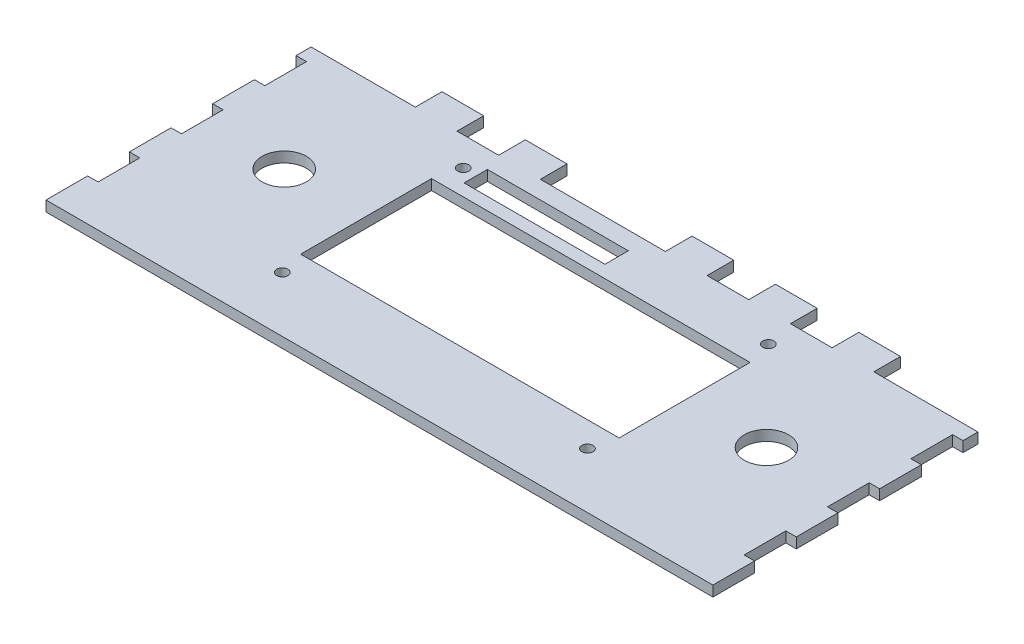
SolidWorks part; units mm, degrees
material "Acrylic (Medium-high impact)"
ref_plane "Front Plane" through (0, 0, 0) normal (0, 0, 1) x (1, 0, 0)
ref_plane "Top Plane" through (0, 0, 0) normal (0, 1, 0) x (1, 0, 0)
ref_plane "Right Plane" through (0, 0, 0) normal (1, 0, 0) x (0, 0, -1)
sketch "Sketch1" plane through (0, 0, 0) normal (0, 1, 0) x (1, 0, 0)
  line L1 (0, 0) -> (203.2, 0)
  line L2 (0, 0) -> (0, 88.9)
  line L3 (0, 88.9) -> (203.2, 88.9)
  line L4 (203.2, 0) -> (203.2, 88.9)
  dimension "D1" = 203.2
  dimension "D2" = 88.9
extrude "Boss-Extrude1" add sketch "Sketch1" along normal blind 3.175
sketch "Sketch2" plane through (0, 3.175, 0) normal (0, 1, 0) x (1, 0, 0)
  line L0 (203.2, 88.9) -> (0, 88.9) construction
  line L1 (19.05, 88.9) -> (31.75, 88.9)
  line L2 (19.05, 88.9) -> (19.05, 80.772)
  line L3 (19.05, 80.772) -> (31.75, 80.772)
  line L4 (31.75, 88.9) -> (31.75, 80.772)
  line L5 (0, 88.9) -> (0, 0) construction
  line L23 (203.2, 0) -> (203.2, 88.9) construction
  line L24 (0, 44.45) -> (203.2, 44.45) construction
  line L45 (0, 50.8) -> (0, 38.1)
  line L46 (0, 76.2) -> (3.175, 76.2)
  line L47 (0, 76.2) -> (0, 63.5)
  line L48 (0, 63.5) -> (3.175, 63.5)
  line L49 (3.175, 76.2) -> (3.175, 63.5)
  line L50 (0, 50.8) -> (3.175, 50.8)
  line L51 (3.175, 50.8) -> (3.175, 38.1)
  line L52 (0, 38.1) -> (3.175, 38.1)
  line L53 (0, 25.4) -> (0, 12.7)
  line L54 (0, 25.4) -> (3.175, 25.4)
  line L55 (3.175, 25.4) -> (3.175, 12.7)
  line L56 (0, 12.7) -> (3.175, 12.7)
  line L57 (44.45, 88.9) -> (44.45, 80.772)
  line L58 (44.45, 88.9) -> (57.15, 88.9)
  line L71 (57.15, 88.9) -> (57.15, 80.772)
  line L72 (44.45, 80.772) -> (57.15, 80.772)
  line L73 (69.85, 88.9) -> (69.85, 80.772)
  line L74 (69.85, 88.9) -> (82.55, 88.9)
  line L75 (82.55, 88.9) -> (82.55, 80.772)
  line L76 (69.85, 80.772) -> (82.55, 80.772)
  line L77 (95.25, 88.9) -> (95.25, 80.772)
  line L78 (95.25, 88.9) -> (107.95, 88.9)
  line L79 (107.95, 88.9) -> (107.95, 80.772)
  line L80 (95.25, 80.772) -> (107.95, 80.772)
  line L81 (120.65, 88.9) -> (120.65, 80.772)
  line L82 (120.65, 88.9) -> (133.35, 88.9)
  line L83 (133.35, 88.9) -> (133.35, 80.772)
  line L84 (120.65, 80.772) -> (133.35, 80.772)
  line L85 (146.05, 88.9) -> (146.05, 80.772)
  line L86 (146.05, 88.9) -> (158.75, 88.9)
  line L87 (158.75, 88.9) -> (158.75, 80.772)
  line L88 (146.05, 80.772) -> (158.75, 80.772)
  line L89 (171.45, 88.9) -> (171.45, 80.772)
  line L90 (171.45, 88.9) -> (184.15, 88.9)
  line L91 (184.15, 88.9) -> (184.15, 80.772)
  line L92 (171.45, 80.772) -> (184.15, 80.772)
  line L97 (196.85, 88.9) -> (196.85, 80.772) [skipped]
  line L98 (196.85, 88.9) -> (209.55, 88.9) [skipped]
  line L99 (209.55, 88.9) -> (209.55, 80.772) [skipped]
  line L100 (196.85, 80.772) -> (209.55, 80.772) [skipped]
  line L129 (101.6, 0) -> (101.6, 88.9) construction
  line L130 (0, 0) -> (203.2, 0) construction
  line L131 (203.2, 12.7) -> (200.025, 12.7)
  line L132 (200.025, 25.4) -> (200.025, 12.7)
  line L133 (203.2, 25.4) -> (200.025, 25.4)
  line L134 (203.2, 25.4) -> (203.2, 12.7)
  line L135 (203.2, 38.1) -> (200.025, 38.1)
  line L136 (200.025, 50.8) -> (200.025, 38.1)
  line L137 (203.2, 50.8) -> (200.025, 50.8)
  line L138 (200.025, 76.2) -> (200.025, 63.5)
  line L139 (203.2, 63.5) -> (200.025, 63.5)
  line L140 (203.2, 76.2) -> (203.2, 63.5)
  line L141 (203.2, 76.2) -> (200.025, 76.2)
  line L142 (203.2, 50.8) -> (203.2, 38.1)
  line L148 (0, 88.9) -> (19.05, 88.9)
  line L149 (0, 88.9) -> (0, 80.772)
  line L150 (0, 80.772) -> (19.05, 80.772)
  line L151 (19.05, 88.9) -> (19.05, 80.772)
  line L152 (184.15, 88.9) -> (203.2, 88.9)
  line L153 (184.15, 88.9) -> (184.15, 80.772)
  line L154 (184.15, 80.772) -> (203.2, 80.772)
  line L155 (203.2, 88.9) -> (203.2, 80.772)
  line L159 (82.55, 88.9) -> (107.95, 88.9)
  line L160 (82.55, 88.9) -> (82.55, 80.772)
  line L161 (82.55, 80.772) -> (107.95, 80.772)
  line L162 (107.95, 88.9) -> (107.95, 80.772)
  point P80 (101.6, 0)
  line M29 (0, 88.9) -> (0, 0)
  line M31 (203.2, 0) -> (203.2, 88.9)
  line M32 (203.2, 88.9) -> (0, 88.9)
  dimension "D1" = 19.05
  dimension "D2" = 12.7
  dimension "D3" = 8.128
  dimension "D5" = 12.7
  dimension "D6" = 12.7
  dimension "D7" = 12.7
  dimension "D8" = 3.175
  dimension "D10" = 12.7
  dimension "D9" = 3
  dimension "D4" = 8
extrude "Cut-Extrude1" cut sketch "Sketch2" against normal through all contours L150 L2 M29 M32 | L4 L2 L3 M32 | L57 L72 L71 M32 | L73 L76 L75 M32 | L81 L84 L83 M32 | L85 L88 L87 M32 | L89 L92 L91 M32 | L91 L154 M31 M32 | L137 L136 L135 M31 | L133 L132 L131 M31 | L56 L55 L54 M29 | L52 L51 L50 M29 | L49 L46 L48 M29 | L75 L161 L77 M32 | L77 L80 L79 M32
sketch "Sketch3" plane through (0, 0, 0) normal (0, -1, 0) x (1, 0, 0)
  line L0 (3.175, -38.1) -> (3.175, -50.8) construction
  line L1 (53.086, -24.511) -> (150.114, -24.511)
  line L2 (53.086, -24.511) -> (53.086, -64.389)
  line L3 (53.086, -64.389) -> (150.114, -64.389)
  line L4 (150.114, -24.511) -> (150.114, -64.389)
  line L6 (0, 0) -> (203.2, 0) construction
  line L7 (59.182, -68.199) -> (102.108, -68.199)
  line L8 (59.182, -68.199) -> (59.182, -75.311)
  line L9 (59.182, -75.311) -> (102.108, -75.311)
  line L10 (102.108, -68.199) -> (102.108, -75.311)
  point P6 (3.175, -44.45)
  point P7 (53.086, -44.45)
  point P8 (101.6, -24.511)
  point P16 (101.6, 0)
  dimension "D1" = 97.028
  dimension "D2" = 39.878
  dimension "D5" = 42.926
  dimension "D6" = 7.112
  dimension "D4" = 3.81
  dimension "D3" = 6.096
extrude "Cut-Extrude2" cut sketch "Sketch3" against normal through all
hole_wizard "M3 Clearance Hole1" positions "Sketch7" profile "Sketch8" hole size "M3" standard "ANSI Metric" end condition through all
sketch "Sketch7" plane through (0, 0, 0) normal (0, -1, 0) x (-1, 0, 0)
  line L1 (-148.082, 72.009) -> (-55.118, 72.009) construction
  line L2 (-148.082, 72.009) -> (-148.082, 16.891) construction
  line L3 (-148.082, 16.891) -> (-55.118, 16.891) construction
  line L4 (-55.118, 72.009) -> (-55.118, 16.891) construction
  line L5 (-53.086, 64.389) -> (-150.114, 64.389) construction
  line L6 (-53.086, 24.511) -> (-53.086, 64.389) construction
  point P0 (-148.082, 72.009)
  point P2 (-148.082, 16.891)
  point P4 (-55.118, 16.891)
  point P6 (-55.118, 72.009)
  point P225 (-101.6, 64.389)
  point P226 (-101.6, 72.009)
  point P229 (-53.086, 44.45)
  point P230 (-55.118, 44.45)
  dimension "D1" = 55.118
  dimension "D2" = 92.964
sketch "Sketch8" plane through (148.082, 0, -72.009) normal (1, 0, 0) x (0, 0, -1)
  line L0 (0, 0) -> (0, 3.175)
  line L1 (0, 3.175) -> (1.7, 3.175)
  line L2 (1.7, 3.175) -> (1.7, 0)
  line L5 (1.7, 0) -> (0, 0)
  line L11 (0, -6.35) -> (0, 107.95) construction
  dimension "Thru Hole Dia." = 3.4
  dimension "Thru Hole Depth" = 3.175
hole_wizard "M12 Clearance Hole1" positions "Sketch5" profile "Sketch6" hole size "M12" standard "ANSI Metric" end condition through all
sketch "Sketch5" plane through (0, 0, 0) normal (0, -1, 0) x (-1, 0, 0)
  line L0 (-150.114, 64.389) -> (-150.114, 24.511) construction
  line L1 (-150.114, 44.45) -> (-200.025, 44.45) construction
  line L2 (-200.025, 50.8) -> (-200.025, 38.1) construction
  line L4 (-53.086, 44.45) -> (-3.175, 44.45) construction
  line L5 (-53.086, 24.511) -> (-53.086, 64.389) construction
  line L6 (-3.175, 38.1) -> (-3.175, 50.8) construction
  point P0 (-175.0695, 44.45)
  point P2 (-28.1305, 44.45)
  point P7 (-150.114, 44.45)
  point P22 (-28.1305, 44.45)
  point P23 (-175.0695, 44.45)
sketch "Sketch6" plane through (175.0695, 0, -44.45) normal (1, 0, 0) x (0, 0, -1)
  line L0 (0, 0) -> (0, 3.175)
  line L1 (0, 3.175) -> (6.75, 3.175)
  line L2 (6.75, 3.175) -> (6.75, 0)
  line L5 (6.75, 0) -> (0, 0)
  line L11 (0, -6.35) -> (0, 107.95) construction
  dimension "Thru Hole Dia." = 13.5
  dimension "Thru Hole Depth" = 3.175
equation "\"screen board width\"= 98mm"
equation "\"screen board height\"= 60mm"
equation "\"lcd width\"= 97mm"
equation "\"lcd height\"= 1.5748in"
equation "\"lcd hole width\"= 93mm"
equation "\"lcd hole height\"= 55mm"
equation "\"D1@Sketch3\"=\"lcd width\""
equation "\"D2@Sketch3\"=\"lcd height\""
equation "\"D1@Sketch7\"=\"lcd hole height\""
equation "\"D2@Sketch7\"=\"lcd hole width\""
